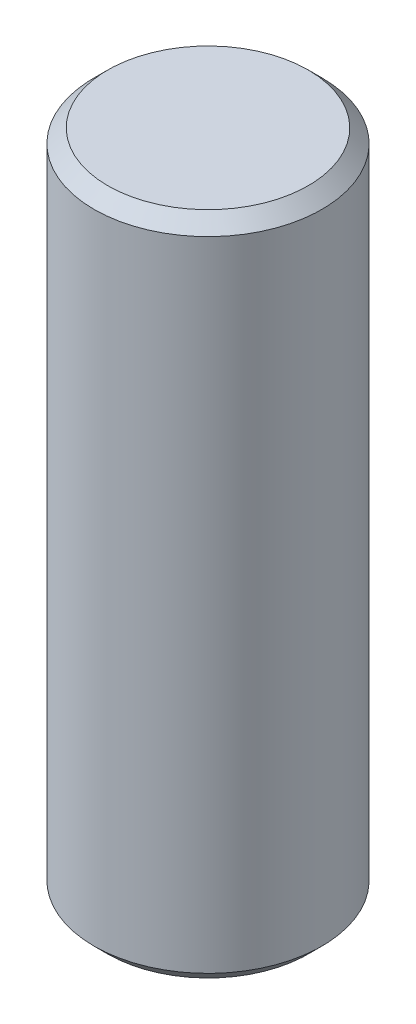
SolidWorks part; units mm, degrees
ref_plane "Front Plane" through (0, 0, 0) normal (0, 0, 1) x (1, 0, 0)
ref_plane "Top Plane" through (0, 0, 0) normal (0, 1, 0) x (1, 0, 0)
ref_plane "Right Plane" through (0, 0, 0) normal (1, 0, 0) x (0, 0, -1)
sketch "Sketch1" plane through (0, 0, 0) normal (0, 1, 0) x (1, 0, 0)
  circle A0 centre (0, 0) radius 2.5
  dimension "D1" = 5
extrude "Boss-Extrude1" add sketch "Sketch1" along normal blind 14.6
chamfer "Chamfer1" distance 0.3 angle 45 2 edges at (0, 0, 2.5) (0, 14.6, 2.5)
